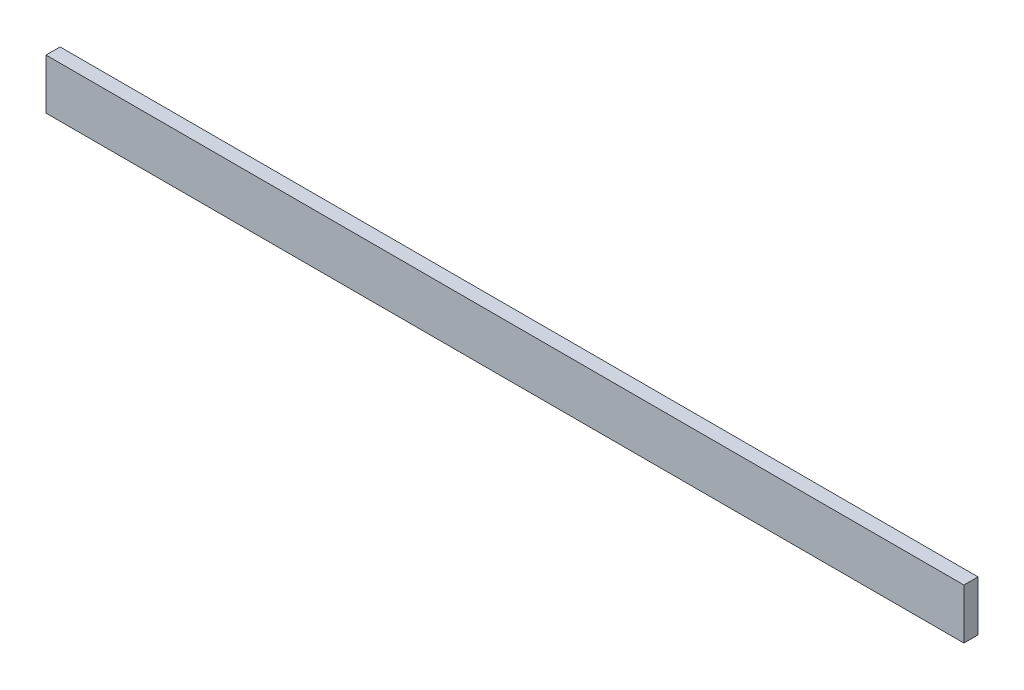
SolidWorks part; units mm, degrees
ref_plane "Front Plane" through (0, 0, 0) normal (0, 0, 1) x (1, 0, 0)
ref_plane "Top Plane" through (0, 0, 0) normal (0, 1, 0) x (1, 0, 0)
ref_plane "Right Plane" through (0, 0, 0) normal (1, 0, 0) x (0, 0, -1)
sketch "Sketch1" plane through (0, 0, 0) normal (0, 0, 1) x (1, 0, 0)
  line L1 (0, 0) -> (488.95, 0)
  line L2 (0, 0) -> (0, 25.4)
  line L3 (0, 25.4) -> (488.95, 25.4)
  line L4 (488.95, 0) -> (488.95, 25.4)
extrude "Boss-Extrude1" add sketch "Sketch1" along normal blind 7.112
sketch "Sketch2" plane through (0, 0, 0) normal (0, 0, 1) x (1, 0, 0)
  line L0 (488.95, 25.4) -> (0, 25.4) construction
  line L1 (0, 0) -> (25.4, 0)
  line L2 (0, 0) -> (0, 25.4)
  line L3 (0, 25.4) -> (25.4, 25.4)
  line L4 (25.4, 0) -> (25.4, 25.4)
extrude "Cut-Extrude1" cut sketch "Sketch2" along normal through all
